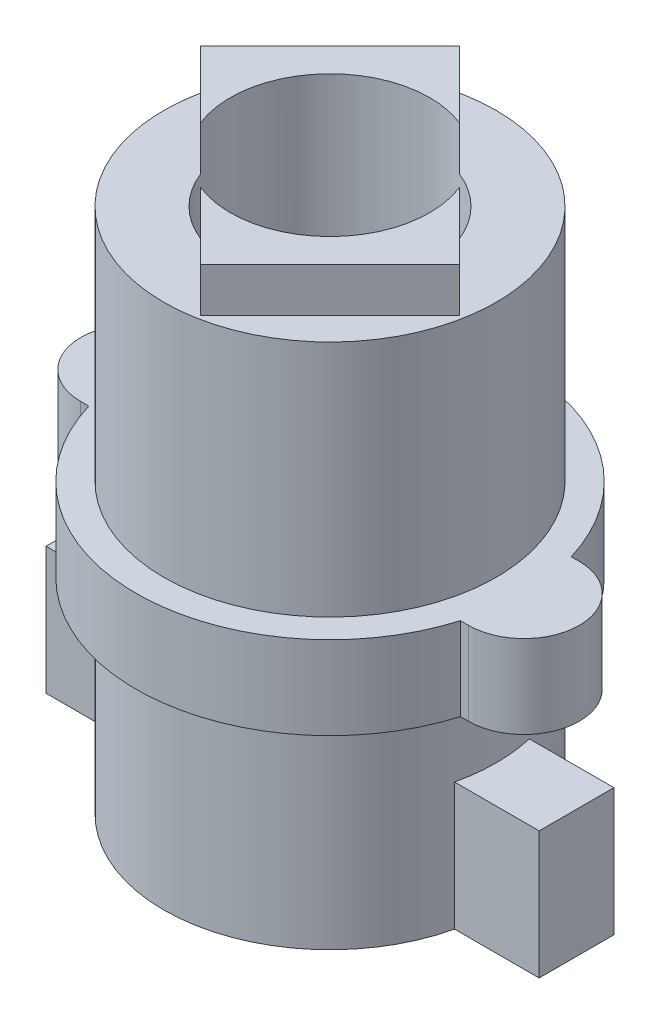
SolidWorks part; units mm, degrees
ref_plane "前视基准面" through (0, 0, 0) normal (0, 0, 1) x (1, 0, 0)
ref_plane "上视基准面" through (0, 0, 0) normal (0, 1, 0) x (1, 0, 0)
ref_plane "右视基准面" through (0, 0, 0) normal (1, 0, 0) x (0, 0, -1)
other "Configuration Table"
sketch "草图1" plane through (0, 0, 0) normal (0, 1, 0) x (1, 0, 0)
  line L1 (-8.9, 1.35) -> (8.9, 1.35)
  line L2 (-8.9, 1.35) -> (-8.9, -1.35)
  line L3 (-8.9, -1.35) -> (8.9, -1.35)
  line L4 (8.9, 1.35) -> (8.9, -1.35)
  line L5 (-8.9, 1.35) -> (8.9, -1.35) construction
  line L6 (-8.9, -1.35) -> (8.9, 1.35) construction
  circle A0 centre (0, 0) radius 6
  point P7 (0, 0)
  point P8 (-8.9, 1.35)
extrude "凸台-拉伸1" add sketch "草图1" along normal blind 4.6 contours L1 L4 L3 L2
sketch "草图2" plane through (0, 0, 0) normal (0, -1, 0) x (-1, 0, 0)
  circle A0 centre (0, 0) radius 6
extrude "凸台-拉伸2" add sketch "草图2" against normal blind 19
sketch "草图4" plane through (0, 19, 0) normal (0, 1, 0) x (1, 0, 0)
  line L1 (-5.7477, 1.078) -> (-3.323, -1.3467)
  line L2 (-5.7477, 1.078) -> (-1.078, 5.7477)
  line L3 (-1.078, 5.7477) -> (1.3467, 3.323)
  line L4 (-3.323, -1.3467) -> (1.3467, 3.323)
  line L5 (-5.7477, 1.078) -> (1.3467, 3.323) construction
  line L6 (-1.078, 5.7477) -> (-3.323, -1.3467) construction
  line L10 (-1.3467, -3.323) -> (1.078, -5.7477)
  line L11 (-1.3467, -3.323) -> (3.323, 1.3467)
  line L12 (3.323, 1.3467) -> (5.7477, -1.078)
  line L13 (1.078, -5.7477) -> (5.7477, -1.078)
  line L14 (-1.3467, -3.323) -> (5.7477, -1.078) construction
  line L15 (3.323, 1.3467) -> (1.078, -5.7477) construction
  point P0 (-2.2005, 2.2005)
  point P5 (2.2005, -2.2005)
extrude "凸台-拉伸3" add sketch "草图4" along normal blind 1.6
sketch "草图6" plane through (0, 0, 0) normal (0, -1, 0) x (1, 0, 0)
  circle A0 centre (0, 0) radius 3.6
ref_plane "Plane1" through (0, 7.4, 0) normal (0, 1, 0) x (1, 0, 0)
sketch "Sketch4" plane through (0, 7.4, 0) normal (0, 1, 0) x (1, 0, 0)
  line L0 (-7, 0) -> (7, 0) construction
  line L3 (-7, 2) -> (7, 2)
  line L4 (-7, -2) -> (7, -2)
  circle A0 centre (0, 0) radius 7
  arc A5 (-7, 2) -> (-7, -2) centre (-7, 0) ccw
  arc A6 (7, -2) -> (7, 2) centre (7, 0) ccw
  point P5 (0, 0)
extrude "Boss-Extrude2" add sketch "Sketch4" along normal blind 3 contours L3 A0 | A0 L0 L3 | L3 A5 L4 A0 | L0 A0 L4 | L4 A0 | L4 A6 L3 A0
extrude "Cut-Extrude2" cut sketch "草图6" against normal through all
